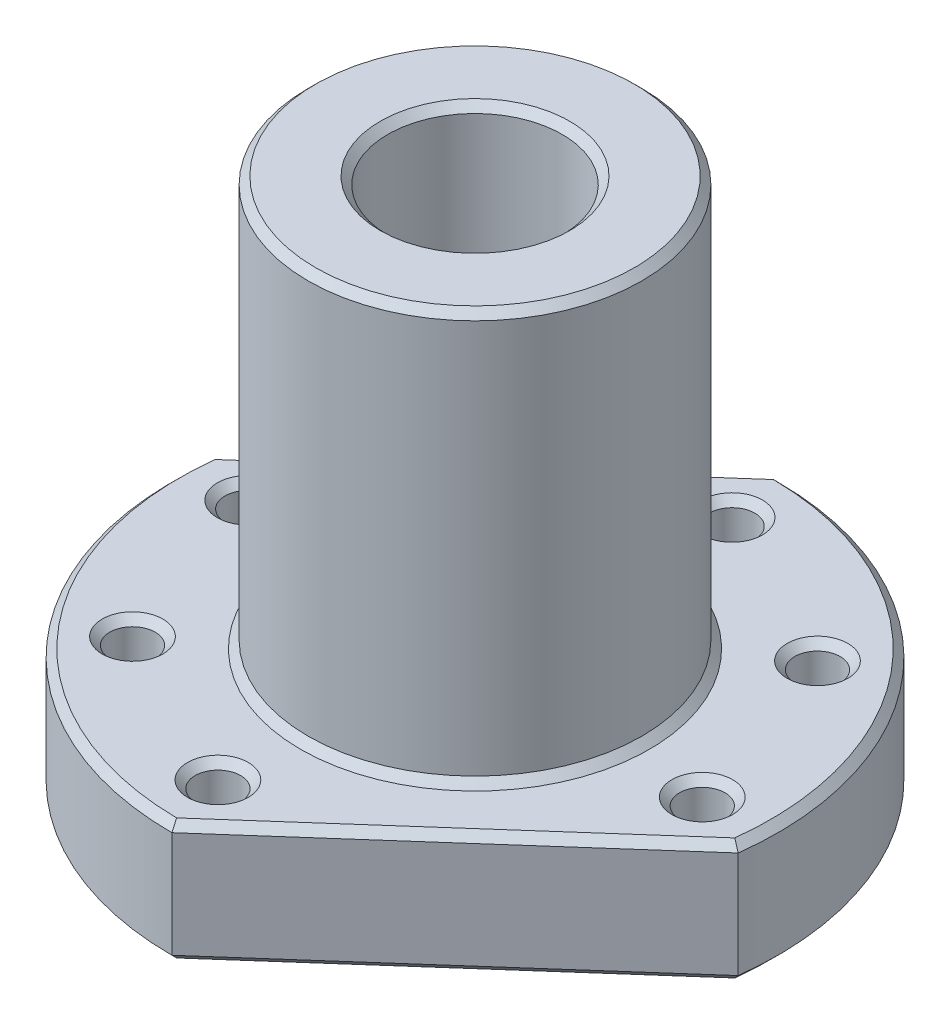
SolidWorks part; units mm, degrees
ref_plane "前视基准面" through (0, 0, 0) normal (0, 0, 1) x (1, 0, 0)
ref_plane "上视基准面" through (0, 0, 0) normal (0, 1, 0) x (1, 0, 0)
ref_plane "右视基准面" through (0, 0, 0) normal (1, 0, 0) x (0, 0, -1)
sketch "草图1" plane through (0, 0, 0) normal (0, 1, 0) x (1, 0, 0)
  line L0 (6.0856, 25.3842) -> (-25.9424, -2.8962)
  line L1 (25.9424, 2.8962) -> (-6.0856, -25.3842)
  arc A0 (-25.9424, -2.8962) -> (-6.0856, -25.3842) centre (0, 0) ccw
  arc A1 (25.9424, 2.8962) -> (6.0856, 25.3842) centre (0, 0) ccw
  point P9 (8.6404, -7.9518)
  dimension "D1" = 15
  dimension "D2" = 15
extrude "凸台-拉伸1" add sketch "草图1" along normal blind 8
sketch "草图2" plane through (0, 8, 0) normal (0, 1, 0) x (1, 0, 0)
  circle A0 centre (0, 0) radius 11
  circle A1 centre (0, 0) radius 5.75
extrude "凸台-拉伸2" add sketch "草图2" along normal blind 27
sketch "草图3" plane through (0, 8, 0) normal (0, 1, 0) x (1, 0, 0)
  circle A0 centre (0, 0) radius 5.75
extrude "切除-拉伸1" cut sketch "草图3" against normal blind 27
sketch "草图4" plane through (0, 8, 0) normal (0, 1, 0) x (1, 0, 0)
  circle A0 centre (0, 0) radius 20
  circle A1 centre (0, 0) radius 43.1681
extrude "切除-拉伸2" cut sketch "草图4" against normal blind 27
sketch "草图5" plane through (0, 8, 0) normal (0, 1, 0) x (1, 0, 0)
  line L0 (14.992, 13.2378) -> (-19.3754, -17.1084) construction
  line L2 (21.4067, -24.2433) -> (-20.5007, 23.2173) construction
  line L7 (-1.637, -26.3449) -> (1.4845, 23.8904) construction
  line L8 (-22.7171, 1.4116) -> (31.25, -1.9418) construction
  arc A1 (19.8446, -2.488) -> (-0.0121, 20) centre (0, 0) ccw construction
  circle A2 centre (0.9834, 15.9697) radius 1.5
  circle A3 centre (11.9877, 10.5969) radius 1.5
  circle A4 centre (15.9697, -0.9834) radius 1.5
  circle A6 centre (-0.9834, -15.9697) radius 1.5
  circle A7 centre (-11.9877, -10.5969) radius 1.5
  circle A8 centre (-15.9697, 0.9834) radius 1.5
  circle A10 centre (-10.5969, 11.9877) radius 1.5 [skipped]
  circle A11 centre (10.5969, -11.9877) radius 1.5 [skipped]
  point P32 (0, 0)
  dimension "D1" = 8
extrude "切除-拉伸3" cut sketch "草图5" against normal through all
chamfer "倒角1" distance 0.5 angle 45 24 edges at (-9.9284, 0, -11.244) (14.992, 0, -13.2378) (-14.992, 0, 13.2378) (9.9284, 0, 11.244) (0, 0, 5.75) (0.9834, 0, -14.4697) (11.9877, 0, -9.0969) (15.9697, 0, 2.4834) (-0.9834, 0, 17.4697) (-11.9877, 0, 12.0969) (-15.9697, 0, 0.5166) (14.992, 8, -13.2378) (-14.992, 8, 13.2378) (-9.9284, 8, -11.244) (9.9284, 8, 11.244) (0, 8, 11) (0.9834, 8, -14.4697) (11.9877, 8, -9.0969) (15.9697, 8, 2.4834) (-0.9834, 8, 17.4697) (-11.9877, 8, 12.0969) (-15.9697, 8, 0.5166) (0, 35, 5.75) (0, 35, 11)
